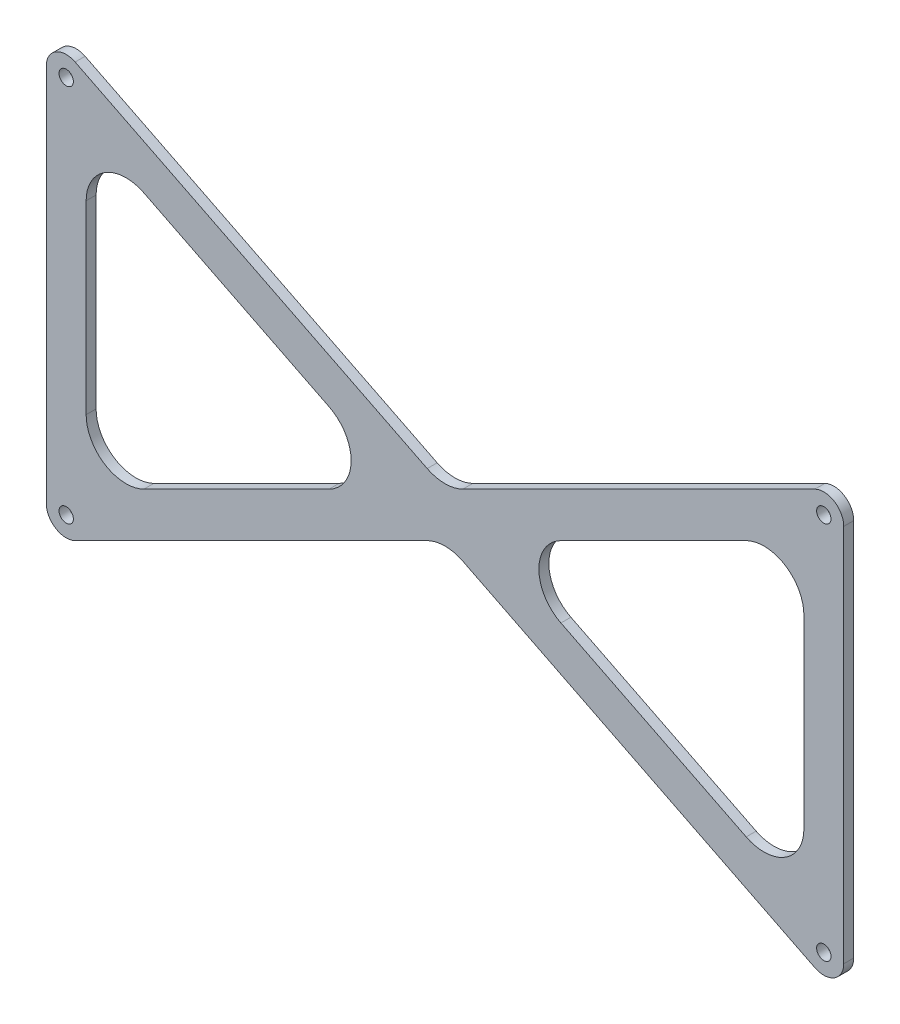
SolidWorks part; units mm, degrees
ref_plane "Front Plane" through (0, 0, 0) normal (0, 0, 1) x (1, 0, 0)
ref_plane "Top Plane" through (0, 0, 0) normal (0, 1, 0) x (1, 0, 0)
ref_plane "Right Plane" through (0, 0, 0) normal (1, 0, 0) x (0, 0, -1)
sketch "Sketch1" plane through (0, 0, 0) normal (0, 0, 1) x (1, 0, 0)
  line L0 (-120.65, -60.325) -> (120.65, 60.325) construction
  line L3 (-114.3, -50.0505) -> (-14.199, 0)
  line L10 (-117.8102, -66.0046) -> (0, -7.0995)
  line L11 (-120.65, 60.325) -> (120.65, -60.325) construction
  line L12 (-117.8102, 66.0046) -> (0, 7.0995)
  line L13 (-114.3, 50.0505) -> (-14.199, 0)
  line L14 (0, 7.0995) -> (117.8102, 66.0046)
  line L15 (0, -7.0995) -> (117.8102, -66.0046)
  line L16 (14.199, 0) -> (114.3, 50.0505)
  line L17 (14.199, 0) -> (114.3, -50.0505)
  line L18 (-127, 60.325) -> (-127, -60.325)
  line L19 (-114.3, 50.0505) -> (-114.3, -50.0505)
  line L20 (127, 60.325) -> (127, -60.325)
  line L21 (114.3, 50.0505) -> (114.3, -50.0505)
  arc A4 (-127, -60.325) -> (-117.8102, -66.0046) centre (-120.65, -60.325) ccw
  arc A5 (127, 60.325) -> (117.8102, 66.0046) centre (120.65, 60.325) ccw
  arc A6 (-117.8102, 66.0046) -> (-127, 60.325) centre (-120.65, 60.325) ccw
  arc A7 (117.8102, -66.0046) -> (127, -60.325) centre (120.65, -60.325) ccw
  point P2 (0, 0)
  point P9 (0, 0)
  point P13 (0, 0)
  point P26 (0, 0)
  dimension "D1" = 254
  dimension "D3" = 6.35
  dimension "D2" = 120.65
extrude "Boss-Extrude1" add sketch "Sketch1" along normal blind 3.175
sketch "Sketch2" plane through (0, 0, 3.175) normal (0, 0, 1) x (1, 0, 0)
  circle A0 centre (-120.65, 60.325) radius 2.286
  circle A1 centre (-120.65, -60.325) radius 2.286
  circle A2 centre (120.65, -60.325) radius 2.286
  circle A3 centre (120.65, 60.325) radius 2.286
  arc A4 (-117.8102, 66.0046) -> (-127, 60.325) centre (-120.65, 60.325) ccw construction
  arc A5 (-127, -60.325) -> (-117.8102, -66.0046) centre (-120.65, -60.325) ccw construction
  arc A6 (117.8102, -66.0046) -> (127, -60.325) centre (120.65, -60.325) ccw construction
  arc A7 (127, 60.325) -> (117.8102, 66.0046) centre (120.65, 60.325) ccw construction
  dimension "D1" = 4.572
extrude "Cut-Extrude1" cut sketch "Sketch2" against normal through all
fillet "Fillet1" radius 12.7 8 edges at (114.3, -50.0505, 1.5875) (114.3, 50.0505, 1.5875) (14.199, 0, 1.5875) (-114.3, -50.0505, 1.5875) (-14.199, 0, 1.5875) (-114.3, 50.0505, 1.5875) (0, 7.0995, 1.5875) (0, -7.0995, 1.5875)
